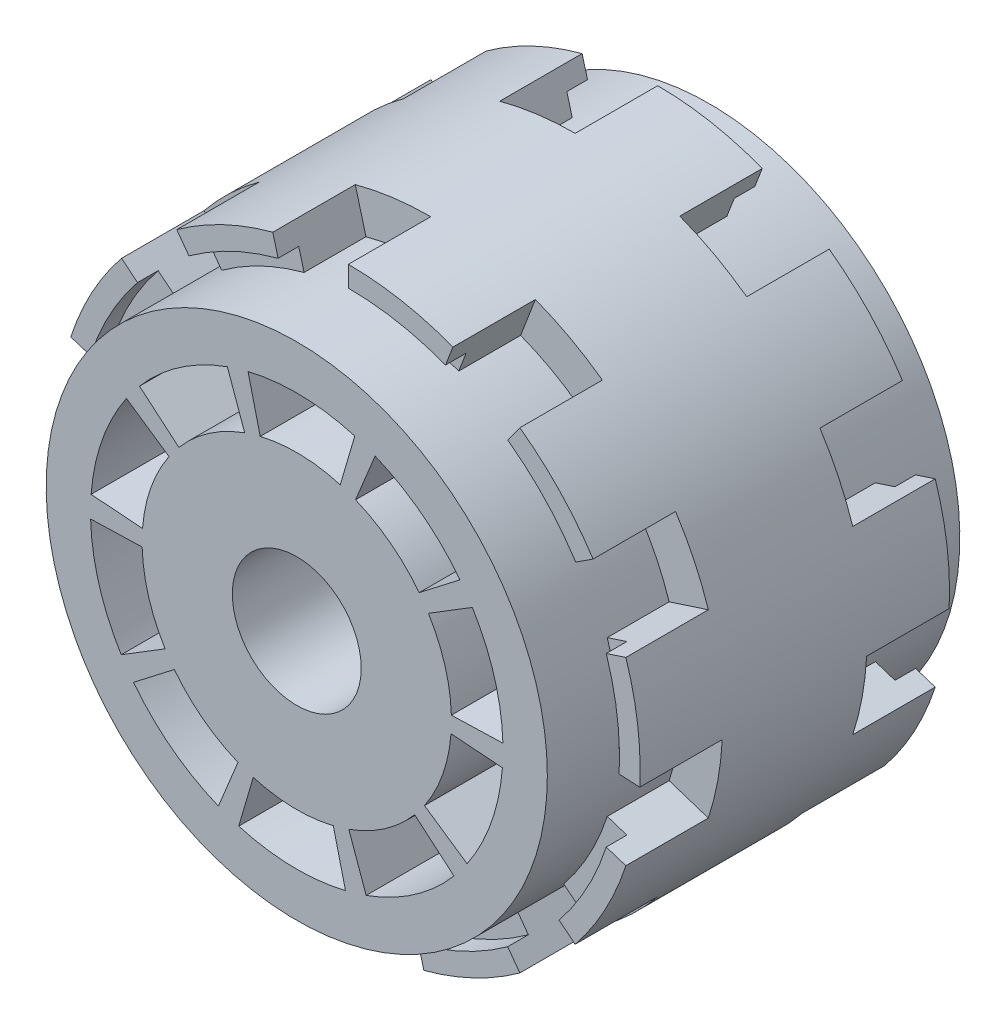
SolidWorks part; units mm, degrees
ref_plane "前视基准面" through (0, 0, 0) normal (0, 0, 1) x (1, 0, 0)
ref_plane "上视基准面" through (0, 0, 0) normal (0, 1, 0) x (1, 0, 0)
ref_plane "右视基准面" through (0, 0, 0) normal (1, 0, 0) x (0, 0, -1)
other "Configuration Table"
sketch "草图1" plane through (0, 0, 0) normal (0, 0, 1) x (1, 0, 0)
  circle A0 centre (0, 0) radius 28.3
  dimension "D1" = 56.6
extrude "凸台-拉伸1" add sketch "草图1" along normal blind 30
sketch "草图4" plane through (0, 0, 30) normal (0, 0, 1) x (1, 0, 0)
  circle A0 centre (0, 0) radius 24.3
  dimension "D1" = 48.6
extrude "凸台-拉伸2" add sketch "草图4" along normal blind 5
sketch "草图5" plane through (0, 0, 0) normal (0, 0, -1) x (-1, 0, 0)
  circle A0 centre (0, 0) radius 24.3
extrude "凸台-拉伸3" add sketch "草图5" along normal blind 5 contours A0
sketch "草图21" plane through (0, 0, 35) normal (0, 0, 1) x (1, 0, 0)
  circle A0 centre (0, 0) radius 6.25
  dimension "D1" = 12.5
extrude "切除-拉伸11" cut sketch "草图21" against normal blind 13
sketch "草图23" plane through (0, 0, 35) normal (0, 0, 1) x (1, 0, 0)
  circle A0 centre (0, 0) radius 2.1
  dimension "D1" = 4.2
extrude "切除-拉伸13" cut sketch "草图23" against normal through all
ref_plane "基准面2" through (0, 0, 11.9) normal (0, 0, 1) x (1, 0, 0)
sketch "草图26" plane through (0, 0, 11.9) normal (0, 0, 1) x (1, 0, 0)
  line L1 (6.9123, -1.3866) -> (4.657, 5.2929)
  line L2 (4.657, 5.2929) -> (-2.2553, 6.6795)
  line L3 (-2.2553, 6.6795) -> (-6.9123, 1.3866)
  line L4 (-6.9123, 1.3866) -> (-4.657, -5.2929)
  line L5 (-4.657, -5.2929) -> (2.2553, -6.6795)
  line L6 (2.2553, -6.6795) -> (6.9123, -1.3866)
  circle A0 centre (0, 0) radius 6.1055 construction
  dimension "D1" = 14.1
extrude "切除-拉伸14" cut sketch "草图26" against normal through all
sketch "草图27" plane through (0, 0, -5) normal (0, 0, -1) x (-1, 0, 0)
  circle A0 centre (0, 0) radius 24.3
  circle A1 centre (0, 0) radius 22
  dimension "D1" = 48.6
extrude "切除-拉伸15" cut sketch "草图27" against normal blind 7 contours A1
sketch "草图31" plane through (0, 0, 0) normal (0, 1, 0) x (1, 0, 0)
  line L2 (0, 8.3904) -> (0, -38.5117) construction
  line L3 (0, -2) -> (0, -7)
  line L5 (0, -2) -> (-22, -2)
  spline S0 degree 2 poles (-22, -2) (-11, -7) (0, -7) knots 0 0 0 0.5 0.5 0.5
  dimension "D1" = 22
  dimension "D2" = 5
revolve "切除-旋转8" cut sketch "草图31" angle 360 about L2
sketch "草图32" plane through (0, 0, 35) normal (0, 0, 1) x (1, 0, 0)
  line L0 (-3.5437, 14.5754) -> (-4.7249, 19.4339)
  line L1 (4.2188, 14.3945) -> (5.6251, 19.1927)
  line L2 (5.7003, 13.8747) -> (7.6004, 18.4995)
  line L3 (11.874, 9.1656) -> (15.8319, 12.2209)
  line L4 (12.767, 7.8743) -> (17.0226, 10.499)
  line L5 (14.9937, 0.4358) -> (19.9916, 0.5811)
  line L6 (14.9571, -1.1338) -> (19.9428, -1.5118)
  line L7 (12.3863, -8.4605) -> (16.5151, -11.2806)
  line L8 (11.4341, -9.7088) -> (15.2455, -12.9451)
  line L9 (5.0478, -14.1251) -> (6.7304, -18.8335)
  line L10 (3.5437, -14.5754) -> (4.7249, -19.4339)
  line L11 (-4.2188, -14.3945) -> (-5.6251, -19.1927)
  line L12 (-5.7003, -13.8747) -> (-7.6004, -18.4995)
  line L13 (-11.874, -9.1656) -> (-15.8319, -12.2209)
  line L14 (-12.767, -7.8743) -> (-17.0226, -10.499)
  line L15 (-14.9937, -0.4358) -> (-19.9916, -0.5811)
  line L16 (-14.9571, 1.1338) -> (-19.9428, 1.5118)
  line L17 (-12.3863, 8.4605) -> (-16.5151, 11.2806)
  line L18 (-11.4341, 9.7088) -> (-15.2455, 12.9451)
  line L19 (-5.0478, 14.1251) -> (-6.7304, 18.8335)
  arc A0 (-4.7249, 19.4339) -> (5.6251, 19.1927) centre (0, 0) cw
  arc A1 (-3.5437, 14.5754) -> (4.2188, 14.3945) centre (0, 0) cw
  arc A2 (7.6004, 18.4995) -> (15.8319, 12.2209) centre (0, 0) cw
  arc A3 (5.7003, 13.8747) -> (11.874, 9.1656) centre (0, 0) cw
  arc A4 (17.0226, 10.499) -> (19.9916, 0.5811) centre (0, 0) cw
  arc A5 (12.767, 7.8743) -> (14.9937, 0.4358) centre (0, 0) cw
  arc A6 (19.9428, -1.5118) -> (16.5151, -11.2806) centre (0, 0) cw
  arc A7 (14.9571, -1.1338) -> (12.3863, -8.4605) centre (0, 0) cw
  arc A8 (15.2455, -12.9451) -> (6.7304, -18.8335) centre (0, 0) cw
  arc A9 (11.4341, -9.7088) -> (5.0478, -14.1251) centre (0, 0) cw
  arc A10 (4.7249, -19.4339) -> (-5.6251, -19.1927) centre (0, 0) cw
  arc A11 (3.5437, -14.5754) -> (-4.2188, -14.3945) centre (0, 0) cw
  arc A12 (-7.6004, -18.4995) -> (-15.8319, -12.2209) centre (0, 0) cw
  arc A13 (-5.7003, -13.8747) -> (-11.874, -9.1656) centre (0, 0) cw
  arc A14 (-17.0226, -10.499) -> (-19.9916, -0.5811) centre (0, 0) cw
  arc A15 (-12.767, -7.8743) -> (-14.9937, -0.4358) centre (0, 0) cw
  arc A16 (-19.9428, 1.5118) -> (-16.5151, 11.2806) centre (0, 0) cw
  arc A17 (-14.9571, 1.1338) -> (-12.3863, 8.4605) centre (0, 0) cw
  arc A18 (-15.2455, 12.9451) -> (-6.7304, 18.8335) centre (0, 0) cw
  arc A19 (-11.4341, 9.7088) -> (-5.0478, 14.1251) centre (0, 0) cw
  point P45 (0, 0)
  dimension "D1" = 20
  dimension "D3" = 15
  dimension "D2" = 30
  dimension "D4" = 10
extrude "切除-拉伸16" cut sketch "草图32" against normal through all
sketch "草图33" plane through (0, 0, 0) normal (0, 0, -1) x (-1, 0, 0)
  line L42 (0, 28.3) -> (0, 24.3)
  line L43 (6.2893, 23.472) -> (7.3246, 27.3357)
  arc A2 (0, 28.3) -> (7.3246, 27.3357) centre (0, 0) cw
  circle A3 centre (0, 0) radius 28.3 construction
  arc A43 (0, 24.3) -> (6.2893, 23.472) centre (0, 0) cw
  dimension "D1" = 24.3
extrude "切除-拉伸17" cut sketch "草图33" against normal blind 8
ref_plane "基准面3" through (0, 0, 8) normal (0, 0, 1) x (1, 0, 0)
pattern_circular "阵列(圆周)3" count 10 over 360 about axis through (0, 0, 0) along (0, 0, 1) of "切除-拉伸17"
sketch "草图37" plane through (0, 0, 30) normal (0, 0, 1) x (1, 0, 0)
  line L2 (0, 24.3) -> (0, 28.3)
  line L3 (-7.3246, 27.3357) -> (-6.2893, 23.472)
  line L4 (0, 24.3) -> (0, 28.3)
  line L5 (-7.3246, 27.3357) -> (-6.2893, 23.472)
  arc A2 (0, 24.3) -> (-6.2893, 23.472) centre (0, 0) ccw
  arc A3 (0, 28.3) -> (-7.3246, 27.3357) centre (0, 0) ccw
  arc A4 (0, 24.3) -> (-6.2893, 23.472) centre (0, 0) ccw
  arc A5 (0, 28.3) -> (-7.3246, 27.3357) centre (0, 0) ccw
  dimension "D1" = 0
extrude "切除-拉伸19" cut sketch "草图37" against normal blind 8
pattern_circular "阵列(圆周)4" count 10 over 360 about axis through (0, 0, 0) along (0, 0, 1) of "切除-拉伸19"
sketch "草图38" plane through (0, 0, 30) normal (0, 0, 1) x (1, 0, 0)
  line L0 (14.2832, 19.6591) -> (16.6343, 22.8952) construction
  line L1 (23.7344, 15.4133) -> (20.3797, 13.2347) construction
  line L2 (14.2832, 19.6591) -> (16.6343, 22.8952) construction
  line L3 (23.7344, 15.4133) -> (20.3797, 13.2347) construction
  line L4 (14.2832, 19.6591) -> (15.4588, 21.2771)
  line L5 (22.057, 14.324) -> (20.3797, 13.2347)
  arc A0 (15.4588, 21.2771) -> (22.057, 14.324) centre (0, 0) cw
  arc A1 (14.2832, 19.6591) -> (20.3797, 13.2347) centre (0, 0) cw
  arc A2 (20.3797, 13.2347) -> (14.2832, 19.6591) centre (0, 0) ccw construction
extrude "切除-拉伸20" cut sketch "草图38" against normal blind 2
pattern_circular "阵列(圆周)5" count 10 over 360 about axis through (0, 0, 30) along (0, 0, -1) of "切除-拉伸20"
sketch "草图39" plane through (0, 0, 0) normal (0, 0, -1) x (-1, 0, 0)
  line L2 (-14.2832, 19.6591) -> (-15.4588, 21.2771)
  line L3 (-22.057, 14.324) -> (-20.3797, 13.2347)
  line L4 (-14.2832, 19.6591) -> (-15.4588, 21.2771)
  line L5 (-22.057, 14.324) -> (-20.3797, 13.2347)
  arc A2 (-15.4588, 21.2771) -> (-22.057, 14.324) centre (0, 0) ccw
  arc A3 (-14.2832, 19.6591) -> (-20.3797, 13.2347) centre (0, 0) ccw
  arc A4 (-15.4588, 21.2771) -> (-22.057, 14.324) centre (0, 0) ccw
  arc A5 (-14.2832, 19.6591) -> (-20.3797, 13.2347) centre (0, 0) ccw
  dimension "D1" = 0
extrude "切除-拉伸21" cut sketch "草图39" against normal blind 2
pattern_circular "阵列(圆周)6" count 10 over 360 about axis through (0, 0, 30) along (0, 0, -1) of "切除-拉伸21"
